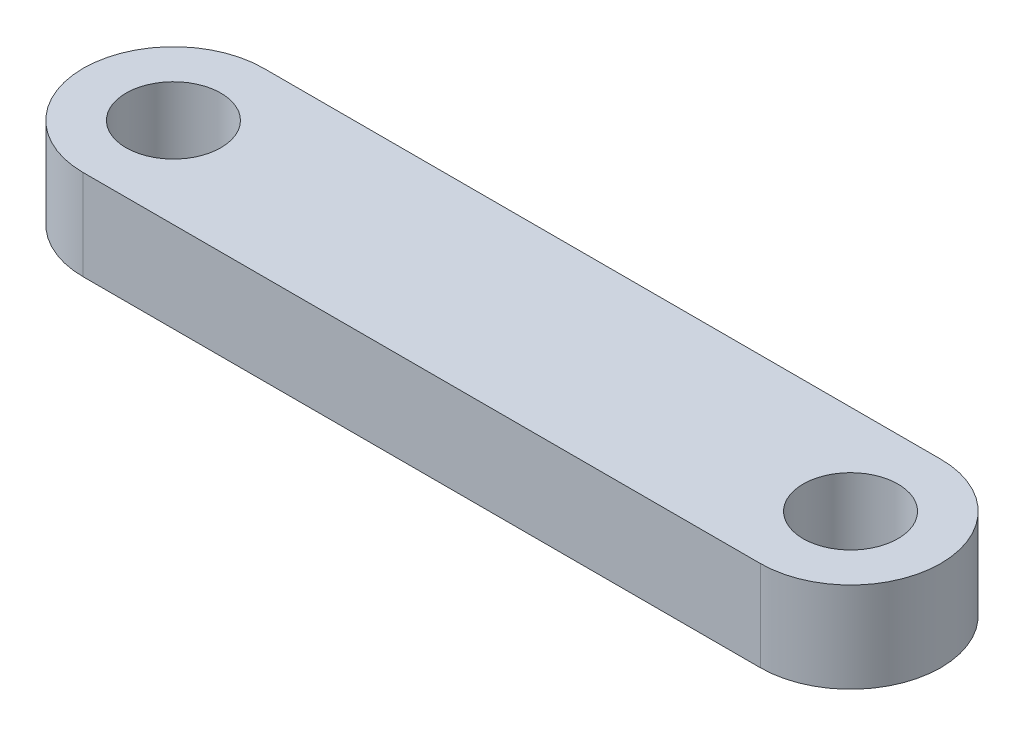
SolidWorks part; units mm, degrees
ref_plane "Front Plane" through (0, 0, 0) normal (0, 0, 1) x (1, 0, 0)
ref_plane "Top Plane" through (0, 0, 0) normal (0, 1, 0) x (1, 0, 0)
ref_plane "Right Plane" through (0, 0, 0) normal (1, 0, 0) x (0, 0, -1)
sketch "Sketch1" plane through (0, 0, 0) normal (0, 1, 0) x (1, 0, 0)
  line L0 (0, 0) -> (15, 0) construction
  line L1 (0, 2) -> (15, 2)
  line L2 (0, -2) -> (15, -2)
  arc A0 (0, 2) -> (0, -2) centre (0, 0) ccw
  arc A1 (15, -2) -> (15, 2) centre (15, 0) ccw
  circle A2 centre (0, 0) radius 1.05
  circle A3 centre (15, 0) radius 1.05
  point P3 (7.5, 0)
  dimension "D2" = 2
  dimension "D4" = 2.1
  dimension "D5" = 2.1
  dimension "D1" = 15
extrude "Boss-Extrude1" add sketch "Sketch1" along normal blind 2
